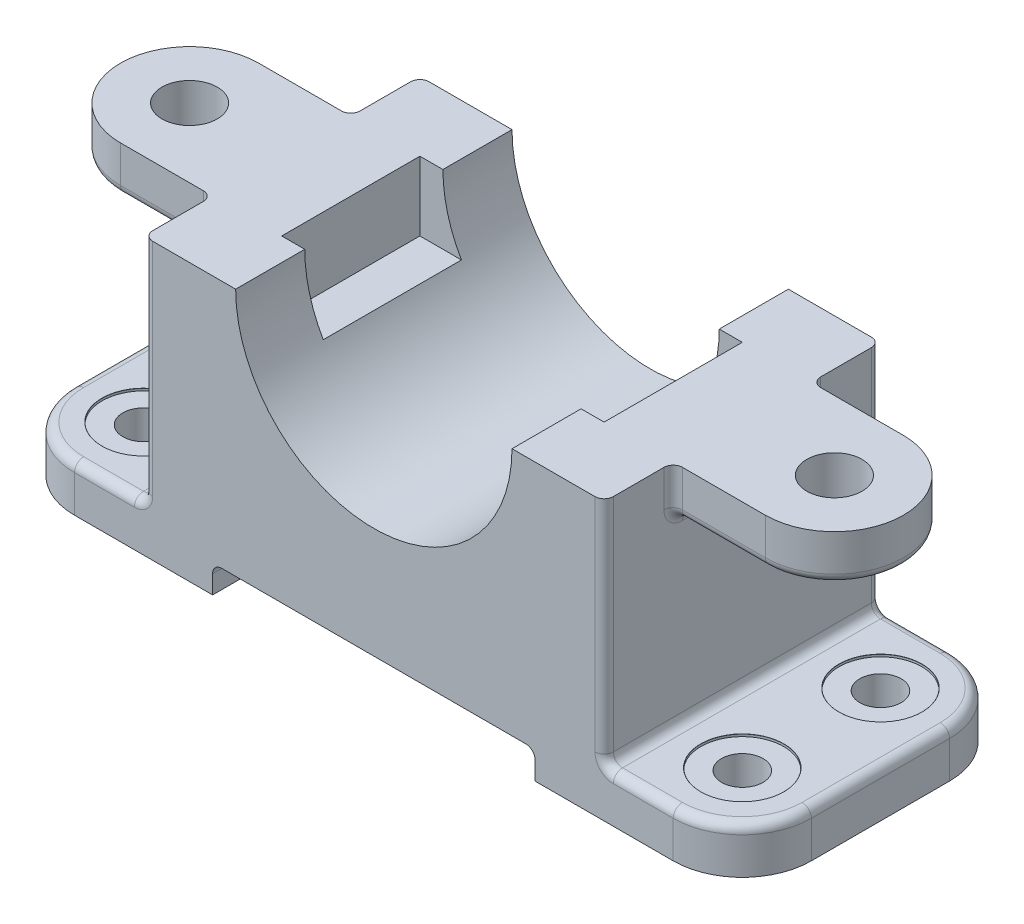
SolidWorks part; units mm, degrees
ref_plane "前视基准面" through (0, 0, 0) normal (0, 0, 1) x (1, 0, 0)
ref_plane "上视基准面" through (0, 0, 0) normal (0, 1, 0) x (1, 0, 0)
ref_plane "右视基准面" through (0, 0, 0) normal (1, 0, 0) x (0, 0, -1)
other "Configuration Table"
sketch "草图1" plane through (0, 0, 0) normal (0, 0, 1) x (1, 0, 0)
  line L0 (35, 0) -> (-35, 0)
  line L1 (-35, 0) -> (-35, -6)
  line L2 (-35, -6) -> (-80, -6)
  line L3 (-80, -6) -> (-80, 4)
  line L4 (-80, 4) -> (-50, 4)
  line L5 (-50, 4) -> (-50, 54)
  line L6 (-50, 54) -> (-30, 54)
  line L7 (0, 59.592) -> (0, -10.2) construction
  line L8 (50, 4) -> (50, 54)
  line L9 (80, 4) -> (50, 4)
  line L10 (80, -6) -> (80, 4)
  line L11 (35, -6) -> (80, -6)
  line L12 (35, 0) -> (35, -6)
  line L13 (30, 54) -> (50, 54)
  arc A0 (-30, 54) -> (30, 54) centre (0, 54) ccw
  point P13 (0, 54)
  point P18 (0, 0)
  dimension "D7" = 30
  dimension "D1" = 6
  dimension "D2" = 10
  dimension "D3" = 160
  dimension "D4" = 70
  dimension "D5" = 60
  dimension "D6" = 100
extrude "凸台-拉伸1" add sketch "草图1" against normal blind 60
sketch "草图2" plane through (0, 54, 0) normal (0, 1, 0) x (1, 0, 0)
  line L0 (-50, 15) -> (-50, 45)
  line L1 (0, 67.7045) -> (0, -8.4999) construction
  line L2 (-50, 60) -> (-50, 0) construction
  line L3 (-50, 45) -> (-70, 45)
  line L5 (-70, 15) -> (-50, 15)
  line L6 (50, 45) -> (70, 45)
  line L7 (50, 15) -> (50, 45)
  line L8 (70, 15) -> (50, 15)
  arc A0 (-70, 45) -> (-70, 15) centre (-70, 30) ccw
  circle A1 centre (-70, 30) radius 6
  circle A2 centre (70, 30) radius 6
  arc A3 (70, 45) -> (70, 15) centre (70, 30) cw
  point P3 (-50, 30)
  dimension "D2" = 15
  dimension "D4" = 12
  dimension "D1" = 20
  dimension "D3" = 30
extrude "凸台-拉伸2" add sketch "草图2" against normal blind 10
fillet "圆角1" radius 15 4 edges at (80, -1, -60) (80, -1, 0) (-80, -1, -60) (-80, -1, 0)
hole_wizard "M8 六角头螺栓的柱形沉头孔1" positions "3D草图2" profile "草图4" counterbore size "M8" standard "GB" end condition through all
sketch3d "3D草图2"
  line L0 (-65, 4, -15) -> (-65, -6, -15) construction
  line L1 (-65, -6, -45) -> (-65, 4, -45) construction
  line L2 (65, -6, -15) -> (65, 4, -15) construction
  line L3 (65, 4, -45) -> (65, -6, -45) construction
  point P0 (-65, 4, -15)
  point P4 (-65, 4, -45)
  point P8 (65, 4, -15)
  point P12 (65, 4, -45)
sketch "草图4" plane through (-65, 4, -15) normal (1, 0, 0) x (0, 0, 1)
  line L0 (0, 0) -> (0, 10)
  line L1 (0, 10) -> (4.5, 10)
  line L3 (4.5, 10) -> (4.5, 0.5)
  line L4 (9, 0.5) -> (4.5, 0.5)
  line L5 (9, 0.5) -> (9, 0.021)
  line L6 (9, 0.021) -> (9.025, 0)
  line L7 (9.025, 0) -> (0, 0)
  line L8 (-9, 0.021) -> (-9.025, 0) construction
  line L11 (0, -6.35) -> (0, 107.95) construction
  dimension "通孔孔直径" = 9
  dimension "通孔孔深度" = 10
  dimension "柱形沉头孔直径" = 18
  dimension "柱形沉头孔深度" = 0.5
  dimension "近端锥形沉头孔直径" = 18.05
  dimension "近端锥形沉头孔角度" = 100
fillet "圆角2" radius 2 30 edges at (-57.5, 4, 0) (-75.6066, 4, -4.3934) (-80, 4, -30) (-75.6066, 4, -55.6066) (-57.5, 4, -60) (57.5, 4, -60) (75.6066, 4, -55.6066) (80, 4, -30) (75.6066, 4, -4.3934) (57.5, 4, 0) (-50, 49, -45) (50, 49, -45) (50, 49, -15) (-50, 49, -15) (-35, 0, -30) (35, 0, -30) (-50, 29, 0) (50, 29, 0) (50, 29, -60) (-50, 29, -60) (-50, 4, -30) (50, 4, -30) (50, 44, -30) (-50, 44, -30) (60, 44, -45) (85, 44, -30) (60, 44, -15) (-60, 44, -15) (-85, 44, -30) (-60, 44, -45)
sketch "草图5" plane through (0, 54, 0) normal (0, 1, 0) x (1, 0, 0)
  line L0 (-30, 0) -> (30, 0) construction
  line L1 (-35, 45) -> (35, 45)
  line L2 (-35, 45) -> (-35, 15)
  line L3 (-35, 15) -> (35, 15)
  line L4 (35, 45) -> (35, 15)
  line L5 (-35, 45) -> (35, 15) construction
  line L6 (-35, 15) -> (35, 45) construction
  point P0 (0, 30)
  point P7 (0, 0)
  point P8 (0, 0)
  dimension "D1" = 30
  dimension "D2" = 70
  dimension "D3" = 30
extrude "切除-拉伸1" cut sketch "草图5" against normal blind 15
